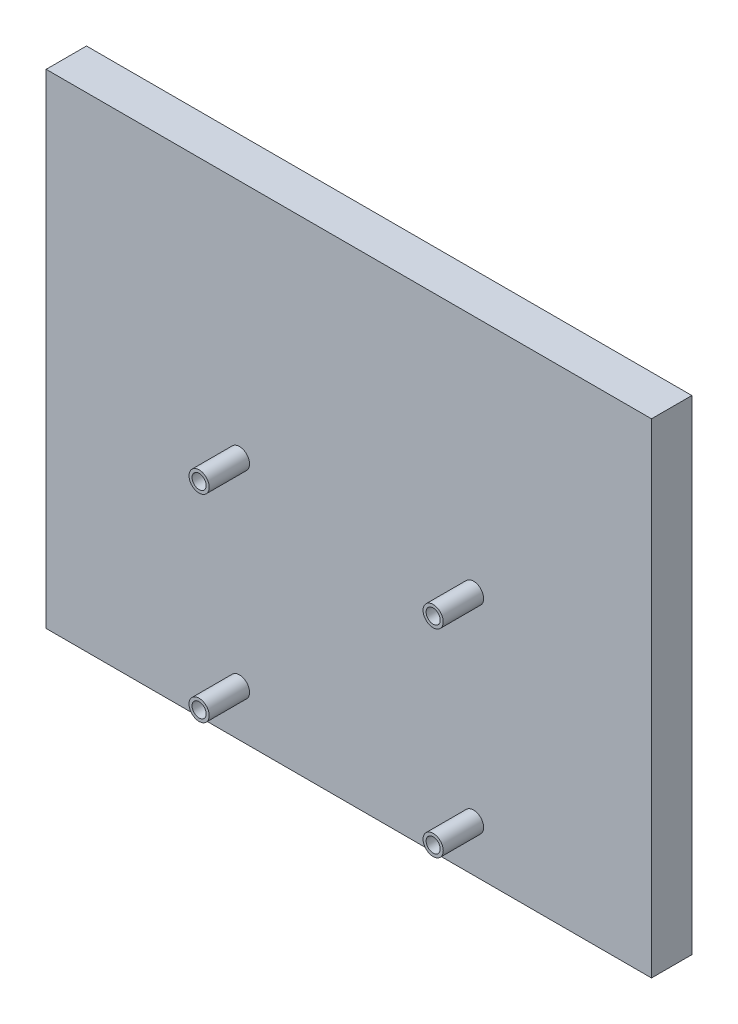
SolidWorks part; units mm, degrees
ref_plane "Front Plane" through (0, 0, 0) normal (0, 0, 1) x (1, 0, 0)
ref_plane "Top Plane" through (0, 0, 0) normal (0, 1, 0) x (1, 0, 0)
ref_plane "Right Plane" through (0, 0, 0) normal (1, 0, 0) x (0, 0, -1)
sketch "Sketch1" plane through (0, 0, 0) normal (0, 0, 1) x (1, 0, 0)
  line L1 (0, 60) -> (150, 60)
  line L2 (0, 60) -> (0, -60)
  line L3 (0, -60) -> (150, -60)
  line L4 (150, 60) -> (150, -60)
  line L5 (0, 60) -> (150, -60) construction
  line L6 (0, -60) -> (150, 60) construction
  point P0 (75, 0)
  point P5 (0, 0)
  dimension "D1" = 150
  dimension "D2" = 120
extrude "Boss-Extrude1" add sketch "Sketch1" along normal blind 10
sketch "Sketch2" plane through (0, 0, 0) normal (-1, 0, 0) x (0, 0, 1)
  line L0 (10, -60) -> (0, -60) construction
  line L2 (0, 60) -> (0, -60) construction
  circle A0 centre (5, 0) radius 4
  circle A1 centre (5, 30) radius 4
  circle A2 centre (5, -30) radius 4
  dimension "D1" = 8
  dimension "D2" = 30
  dimension "D3" = 30
  dimension "D4" = 30
  dimension "D5" = 5
extrude "Cut-Extrude1" cut sketch "Sketch2" against normal blind 30
sketch "Croquis4" plane through (0, 0, 10) normal (0, 0, 1) x (1, 0, 0)
  line L1 (0, -60) -> (150, -60) construction
  line L2 (150, -60) -> (150, 60) construction
  line L5 (150, 60) -> (0, 60) construction
  circle A0 centre (47.9001, 0.5) radius 2.5
  circle A1 centre (105.9, 0.6156) radius 2.5
  circle A2 centre (105.9, -48.5) radius 2.5
  circle A3 centre (47.9001, -48.5) radius 2.5
  dimension "D5" = 5
  dimension "D6" = 59.3844
  dimension "D1" = 57.9999
  dimension "D2" = 49
  dimension "D3" = 11.5
  dimension "D4" = 44.1
extrude "Saliente-Extruir2" add sketch "Croquis4" along normal blind 10
sketch "Croquis5" plane through (0, 0, 20) normal (0, 0, 1) x (1, 0, 0)
  circle A0 centre (47.9001, 0.5) radius 1.75
  circle A1 centre (47.9001, -48.5) radius 1.75
  circle A2 centre (105.9, -48.5) radius 1.75
  circle A3 centre (105.9, 0.6156) radius 1.75
  dimension "D1" = 3.5
extrude "Cortar-Extruir1" cut sketch "Croquis5" against normal blind 9
